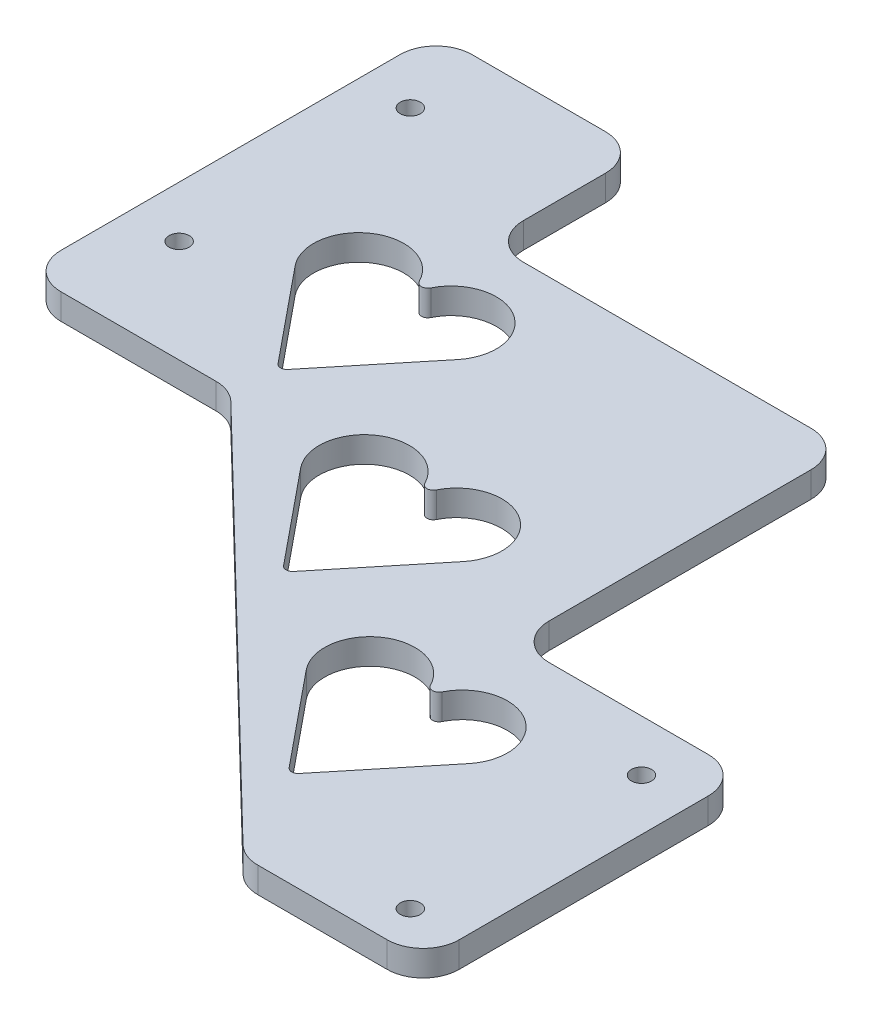
SolidWorks part; units mm, degrees
material "PC High Viscosity"
ref_plane "Front Plane" through (0, 0, 0) normal (0, 0, 1) x (1, 0, 0)
ref_plane "Top Plane" through (0, 0, 0) normal (0, 1, 0) x (1, 0, 0)
ref_plane "Right Plane" through (0, 0, 0) normal (1, 0, 0) x (0, 0, -1)
sketch "Sketch1" plane through (0, 0, 0) normal (0, 1, 0) x (1, 0, 0)
  line L0 (139.7, 107.95) -> (139.7, 25.4)
  line L2 (0, 44.45) -> (0, 107.95)
  line L3 (50.8, 107.95) -> (139.7, 107.95)
  line L4 (196.85, 0) -> (196.85, 25.4)
  line L5 (139.7, 25.4) -> (196.85, 25.4)
  line L7 (152.4, -53.975) -> (196.85, -53.975)
  line L8 (196.85, -53.975) -> (196.85, 0)
  line L10 (50.8, 44.45) -> (0, 44.45)
  line L11 (50.8, 44.45) -> (152.4, -53.975)
  line L12 (0, 107.95) -> (0, 0) construction
  line L13 (0, 0) -> (196.85, 0) construction
  line L14 (0, 107.95) -> (0, 146.05)
  line L15 (0, 146.05) -> (50.8, 146.05)
  line L16 (50.8, 146.05) -> (50.8, 107.95)
  circle A1 centre (184.15, 12.7) radius 2.4892
  circle A2 centre (12.7, 69.85) radius 2.4892
  circle A7 centre (184.15, -44.45) radius 2.4892
  circle A8 centre (12.7, 127) radius 2.4892
  dimension "D3" = 38.1
  dimension "D6" = 12.7
  dimension "D10" = 4.9784
  dimension "D2" = 196.85
  dimension "D4" = 12.7
  dimension "D5" = 12.7
  dimension "D7" = 57.15
  dimension "D8" = 161.925
  dimension "D9" = 107.95
  dimension "D11" = 50.8
  dimension "D12" = 57.15
  dimension "D13" = 57.15
  dimension "D14" = 38.1
  dimension "D15" = 25.4
  dimension "D16" = 101.6
  dimension "D17" = 25.4
  dimension "D18" = 50.8
extrude "Boss-Extrude1" add sketch "Sketch1" along normal mid plane 6.35
sketch "Sketch3" plane through (0, 3.175, 0) normal (0, 1, 0) x (1, 0, 0)
  line L0 (25.4, 44.45) -> (25.4, 146.05)
  line L1 (171.45, 25.4) -> (171.45, -53.975)
  line L2 (130.175, 98.425) -> (41.275, 98.425)
  line L3 (41.275, 98.425) -> (41.275, 136.525)
  line L4 (41.275, 136.525) -> (9.525, 136.525)
  line L5 (9.525, 136.525) -> (9.525, 53.975)
  line L6 (9.525, 53.975) -> (54.6571, 53.975)
  line L7 (54.6571, 53.975) -> (156.2571, -44.45)
  line L8 (156.2571, -44.45) -> (187.325, -44.45)
  line L9 (187.325, -44.45) -> (187.325, 15.875)
  line L10 (50.8, 107.95) -> (50.8, 146.05)
  line L11 (50.8, 146.05) -> (0, 146.05)
  line L12 (0, 146.05) -> (0, 44.45)
  line L13 (0, 44.45) -> (50.8, 44.45)
  line L14 (50.8, 44.45) -> (152.4, -53.975)
  line L15 (152.4, -53.975) -> (196.85, -53.975)
  line L16 (196.85, -53.975) -> (196.85, 25.4)
  line L17 (196.85, 25.4) -> (139.7, 25.4)
  line L18 (139.7, 25.4) -> (139.7, 107.95)
  line L19 (139.7, 107.95) -> (50.8, 107.95)
  line L20 (50.8, 107.95) -> (50.8, 146.05)
  line L21 (50.8, 146.05) -> (0, 146.05)
  line L22 (0, 146.05) -> (0, 44.45)
  line L23 (0, 44.45) -> (50.8, 44.45)
  line L24 (50.8, 44.45) -> (152.4, -53.975)
  line L25 (152.4, -53.975) -> (196.85, -53.975)
  line L26 (196.85, -53.975) -> (196.85, 25.4)
  line L27 (196.85, 25.4) -> (139.7, 25.4)
  line L28 (139.7, 25.4) -> (139.7, 107.95)
  line L29 (139.7, 107.95) -> (50.8, 107.95)
  line L30 (187.325, 15.875) -> (130.175, 15.875)
  line L31 (130.175, 15.875) -> (130.175, 98.425)
  line L32 (41.275, 98.425) -> (25.4, 53.975) construction
  line L33 (54.6571, 53.975) -> (130.175, 98.425) construction
  line L34 (77.3125, 67.31) -> (66.675, 98.425) construction
  line L35 (92.4161, 76.2) -> (105.4571, 4.7625) construction
  line L36 (105.4571, 4.7625) -> (130.175, 15.875) construction
  line L37 (97.4586, 48.5775) -> (130.175, 40.386) construction
  line L38 (171.7911, -44.45) -> (130.175, 15.875) construction
  line L39 (41.275, 107.865) -> (22.0286, 53.975)
  line L40 (80.3168, 68.3371) -> (69.6793, 99.4521)
  line L41 (56.2676, 51.2388) -> (131.7855, 95.6888)
  line L42 (89.2927, 75.6298) -> (103.0617, 0.2045)
  line L43 (103.0617, 0.2045) -> (131.4769, 12.9792)
  line L44 (96.6875, 45.4976) -> (130.175, 37.113)
  line L45 (174.4045, -42.6471) -> (132.7884, 17.6779)
  line L46 (44.6464, 98.425) -> (28.39, 52.9071)
  line L47 (74.3082, 66.2829) -> (63.3196, 98.425)
  line L48 (48.3979, 53.975) -> (128.5645, 101.1612)
  line L49 (95.5394, 76.7702) -> (107.8525, 9.3205)
  line L50 (107.8525, 9.3205) -> (130.175, 19.3561)
  line L51 (98.2297, 51.6574) -> (130.9461, 43.4659)
  line L52 (169.1776, -46.2529) -> (127.5616, 14.0721)
  line L53 (38.285, 99.4929) -> (22.41, 55.0429) construction
  line L54 (74.3082, 66.2829) -> (63.6707, 97.3979) construction
  line L55 (53.0466, 56.7112) -> (128.5645, 101.1612) construction
  line L56 (96.6875, 45.4976) -> (129.4039, 37.3061) construction
  line L57 (107.8525, 9.3205) -> (128.8731, 18.7708) construction
  line L58 (44.265, 97.3571) -> (28.39, 52.9071) construction
  circle A1 centre (12.7, 127) radius 2.4892
  circle A2 centre (12.7, 127) radius 2.4892
  circle A3 centre (184.15, -44.45) radius 2.4892
  circle A4 centre (184.15, -44.45) radius 2.4892
  circle A5 centre (12.7, 69.85) radius 2.4892
  circle A6 centre (12.7, 69.85) radius 2.4892
  circle A7 centre (184.15, 12.7) radius 2.4892
  circle A8 centre (184.15, 12.7) radius 2.4892
  dimension "D6" = 25.4
  dimension "D7" = 25.4
  dimension "D9" = 25.4
  dimension "D10" = 13.335
  dimension "D11" = 43.815
  dimension "D12" = 58.039
  dimension "D1" = 0
  dimension "D2" = 0
  dimension "D3" = 0
  dimension "D4" = 0
  dimension "D5" = 0
  dimension "D8" = 9.525
  dimension "D13" = 3.175
  dimension "D14" = 3.175
extrude "Cut-Extrude1" [suppressed] cut sketch "Sketch3" against normal through all contours L6 L48 L47 L2 L46 | L40 L48 L2 | L49 L51 L31 L41 | L42 L41 L7 | L49 L50 L31 L44 | L8 L52 L43 L7 | L45 L1 L30 | L39 L3 L4 L0
fillet "Fillet1" [suppressed] radius 6.35
fillet "Fillet2" radius 8.89 10 edges at (50.8, 0, -107.95) (139.7, 0, -25.4) (196.85, 0, -25.4) (196.85, 0, 53.975) (152.4, 0, 53.975) (50.8, 0, -44.45) (0, 0, -44.45) (0, 0, -146.05) (50.8, 0, -146.05) (139.7, 0, -107.95)
sketch "Sketch4" plane through (0, 3.175, 0) normal (0, 1, 0) x (1, 0, 0)
  line L0 (32.261, 78.9647) -> (52.3428, 54.3724)
  line L1 (52.3428, 54.3724) -> (72.4246, 78.9647)
  line L2 (50.9492, 90.9327) -> (52.3428, 88.0799)
  line L3 (52.3428, 88.0799) -> (53.7365, 90.9327)
  line L4 (76.2021, 36.3968) -> (96.2839, 11.8045)
  line L5 (96.2839, 11.8045) -> (116.3657, 36.3968)
  line L6 (94.8902, 48.3648) -> (96.2839, 45.512)
  line L7 (96.2839, 45.512) -> (97.6775, 48.3648)
  line L8 (120.1431, -6.1711) -> (140.225, -30.7634)
  line L9 (140.225, -30.7634) -> (160.3068, -6.1711)
  line L10 (138.8313, 5.7969) -> (140.225, 2.9441)
  line L11 (140.225, 2.9441) -> (141.6186, 5.7969)
  line L12 (140.225, -30.7634) -> (52.3428, 54.3724) construction
  line L13 (53.3856, 41.9452) -> (149.8144, -51.4702) construction
  arc A0 (32.261, 78.9647) -> (50.9492, 90.9327) centre (40.9128, 86.0297) cw
  arc A1 (72.4246, 78.9647) -> (53.7365, 90.9327) centre (63.7728, 86.0297) ccw
  arc A2 (76.2021, 36.3968) -> (94.8902, 48.3648) centre (84.8539, 43.4618) cw
  arc A3 (116.3657, 36.3968) -> (97.6775, 48.3648) centre (107.7139, 43.4618) ccw
  arc A4 (120.1431, -6.1711) -> (138.8313, 5.7969) centre (128.795, 0.8939) cw
  arc A5 (160.3068, -6.1711) -> (141.6186, 5.7969) centre (151.655, 0.8939) ccw
  dimension "D1" = 31.75
  dimension "D2" = 3.175
  dimension "D3" = 22.86
  dimension "D4" = 31.75
  dimension "D5" = 3.175
  dimension "D6" = 22.86
  dimension "D7" = 31.75
  dimension "D8" = 3.175
  dimension "D9" = 22.86
extrude "Cut-Extrude2" cut sketch "Sketch4" against normal through all
fillet "Fillet3" radius 1.5875 6 edges at (52.3428, 0, -88.0799) (52.3428, 0, -54.3724) (140.225, 0, -2.9441) (140.225, 0, 30.7634) (96.2839, 0, -11.8045) (96.2839, 0, -45.512)
